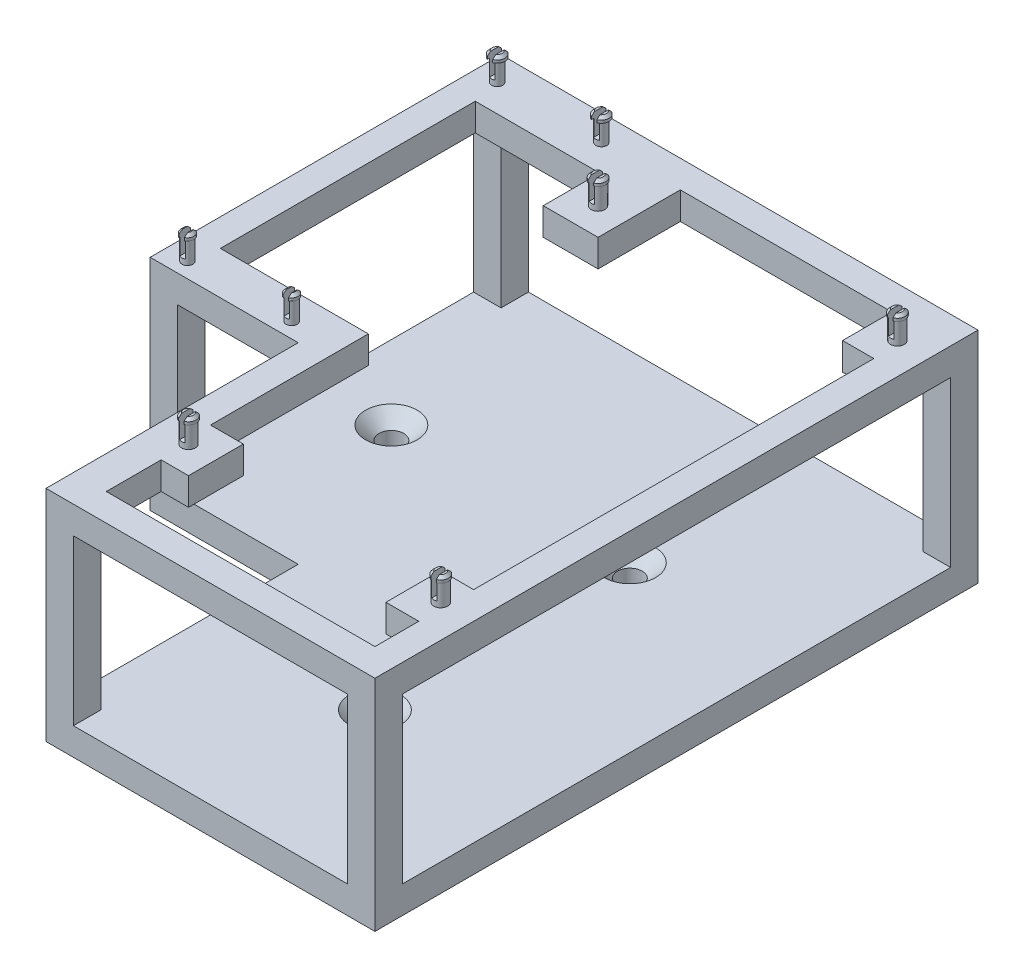
SolidWorks part; units mm, degrees
material "ABS"
ref_plane "Front Plane" through (0, 0, 0) normal (0, 0, 1) x (1, 0, 0)
ref_plane "Top Plane" through (0, 0, 0) normal (0, 1, 0) x (1, 0, 0)
ref_plane "Right Plane" through (0, 0, 0) normal (1, 0, 0) x (0, 0, -1)
sketch "Sketch1" plane through (0, 0, 0) normal (0, 0, 1) x (1, 0, 0)
  line L0 (0, 0) -> (10, 0)
  line L1 (10, 0) -> (55, 2.3584)
  line L2 (55, 2.3584) -> (54.7387, 7.3447)
  line L3 (54.7387, 7.3447) -> (10, 5)
  line L4 (10, 5) -> (5, 5)
  line L5 (0, 0) -> (0, 29)
  line L6 (0, 29) -> (60, 29)
  line L7 (60, 29) -> (60, 24)
  line L8 (60, 24) -> (5, 24)
  line L9 (5, 24) -> (5, 5)
  line L10 (10, 0) -> (45.1286, 0) construction
  point P8 (7.5, 5)
  dimension "D1" = 5
  dimension "D2" = 10
  dimension "D3" = 5
  dimension "D4" = 5
  dimension "D5" = 3
  dimension "D6" = 55
  dimension "D7" = 19
  dimension "D8" = 5
  dimension "D9" = 60
extrude "Boss-Extrude1" add sketch "Sketch1" along normal mid plane 30
sketch "Sketch2" plane through (0, 29, 0) normal (0, 1, 0) x (1, 0, 0)
  line L0 (0, -15) -> (0, 15) construction
  line L1 (0, -55) -> (60, -55)
  line L2 (0, -55) -> (0, 55)
  line L3 (0, 55) -> (60, 55)
  line L4 (60, -55) -> (60, 55)
  line L5 (0, -55) -> (60, 55) construction
  line L6 (0, 55) -> (60, -55) construction
  point P0 (30, 0)
  dimension "D1" = 60
  dimension "D2" = 110
extrude "Boss-Extrude2" add sketch "Sketch2" against normal blind 5
sketch "Sketch3" plane through (0, 29, 0) normal (0, 1, 0) x (1, 0, 0)
  line L1 (56.5, -51) -> (3.5, -51) construction
  line L2 (56.5, -51) -> (56.5, 51) construction
  line L3 (56.5, 51) -> (3.5, 51) construction
  line L4 (3.5, -51) -> (3.5, 51) construction
  line L5 (56.5, -51) -> (3.5, 51) construction
  line L6 (56.5, 51) -> (3.5, -51) construction
  circle A0 centre (54, -37) radius 1.25
  point P0 (30, 0)
  dimension "D5" = 2.5
  dimension "D6" = 2.5
  dimension "D1" = 102
  dimension "D2" = 53
  dimension "D3" = 30
  dimension "D7" = 14
extrude "Boss-Extrude3" add sketch "Sketch3" along normal blind 4
ref_plane "Plane1" through (30, 0, 0) normal (1, 0, 0) x (0, 0, -1)
sketch "Sketch4" plane through (0, 33, 0) normal (0, 1, 0) x (1, 0, 0)
  circle A0 centre (54, -37) radius 1.405
  dimension "D1" = 2.81
extrude "Boss-Extrude4" add sketch "Sketch4" along normal blind 1
chamfer "Chamfer1" distance 0.5 angle 45 1 edges at (54, 34, 38.405)
sketch "Sketch5" plane through (0, 34, 0) normal (0, 1, 0) x (1, 0, 0)
  line L1 (53.5, -38.6304) -> (54.5, -38.6304)
  line L2 (53.5, -38.6304) -> (53.5, -35.3696)
  line L3 (53.5, -35.3696) -> (54.5, -35.3696)
  line L4 (54.5, -38.6304) -> (54.5, -35.3696)
  line L5 (53.5, -38.6304) -> (54.5, -35.3696) construction
  line L6 (53.5, -35.3696) -> (54.5, -38.6304) construction
  point P0 (54, -37)
  dimension "D1" = 1
extrude "Cut-Extrude1" cut sketch "Sketch5" against normal blind 4
sketch "Sketch7" plane through (0, 29, 0) normal (0, 1, 0) x (1, 0, 0)
  line L1 (3.2, 51) -> (56.8, 51) construction
  line L2 (3.2, 51) -> (3.2, -51) construction
  line L4 (56.8, 51) -> (56.8, -51) construction
  line L5 (3.2, 51) -> (56.8, -51) construction
  line L6 (3.2, -51) -> (56.8, 51) construction
  line L7 (3.2, -51) -> (56.8, -51) construction
  circle A0 centre (54.3, 46) radius 1.25
  circle A1 centre (5.7, 40) radius 1.25
  circle A2 centre (54, -37) radius 1.25 construction
  circle A3 centre (54, -37) radius 1.25 construction
  point P0 (30, 0)
  dimension "D5" = 2.5
  dimension "D6" = 2.5
  dimension "D2" = 30
  dimension "D3" = 102
  dimension "D4" = 53.6
  dimension "D7" = 2.5
  dimension "D8" = 5
  dimension "D9" = 11
  dimension "D10" = 2.5
extrude "Boss-Extrude5" add sketch "Sketch7" along normal blind 4
sketch "Sketch8" plane through (0, 33, 0) normal (0, 1, 0) x (1, 0, 0)
  circle A0 centre (5.7, 40) radius 1.405
  circle A1 centre (54.3, 46) radius 1.405
  dimension "D1" = 2.81
  dimension "D2" = 2.81
extrude "Boss-Extrude6" add sketch "Sketch8" along normal blind 1
chamfer "Chamfer2" distance 0.5 angle 45 2 edges at (54.3, 34, -44.595) (5.7, 34, -38.595)
sketch "Sketch9" plane through (0, 34, 0) normal (0, 1, 0) x (1, 0, 0)
  line L1 (5.2, 42.0497) -> (6.2, 42.0497)
  line L2 (5.2, 42.0497) -> (5.2, 37.9503)
  line L3 (5.2, 37.9503) -> (6.2, 37.9503)
  line L4 (6.2, 42.0497) -> (6.2, 37.9503)
  line L5 (5.2, 42.0497) -> (6.2, 37.9503) construction
  line L6 (5.2, 37.9503) -> (6.2, 42.0497) construction
  line L7 (53.8, 43.593) -> (54.8, 43.593)
  line L8 (53.8, 43.593) -> (53.8, 48.407)
  line L9 (53.8, 48.407) -> (54.8, 48.407)
  line L10 (54.8, 43.593) -> (54.8, 48.407)
  line L11 (53.8, 43.593) -> (54.8, 48.407) construction
  line L12 (53.8, 48.407) -> (54.8, 43.593) construction
  point P0 (5.7, 40)
  point P5 (54.3, 46)
  dimension "D1" = 1
  dimension "D2" = 1
extrude "Cut-Extrude2" cut sketch "Sketch9" against normal blind 4
sketch "Sketch10" plane through (0, 29, 0) normal (0, 1, 0) x (1, 0, 0)
  line L0 (4.75, -35) -> (4.75, -28.2355) construction
  line L1 (0, -55) -> (0, 55) construction
  line L2 (55.25, -37) -> (55.25, -32.1392) construction
  circle A0 centre (6, -35) radius 1.25
  circle A1 centre (5.7, 40) radius 1.405 construction
  circle A2 centre (54, -37) radius 1.25 construction
  circle A3 centre (54, -37) radius 1.25 construction
  dimension "D1" = 2.81
  dimension "D3" = 2.5
  dimension "D2" = 75
  dimension "D4" = 4.75
extrude "Boss-Extrude7" add sketch "Sketch10" along normal blind 4
sketch "Sketch11" plane through (0, 33, 0) normal (0, 1, 0) x (1, 0, 0)
  circle A0 centre (6, -35) radius 1.405
  dimension "D1" = 2.81
extrude "Boss-Extrude8" add sketch "Sketch11" along normal blind 1
chamfer "Chamfer3" distance 0.5 angle 45 1 edges at (6, 34, 36.405)
sketch "Sketch12" plane through (0, 34, 0) normal (0, 1, 0) x (1, 0, 0)
  line L1 (6.5, -36.8935) -> (5.5, -36.8935)
  line L2 (6.5, -36.8935) -> (6.5, -33.1065)
  line L3 (6.5, -33.1065) -> (5.5, -33.1065)
  line L4 (5.5, -36.8935) -> (5.5, -33.1065)
  line L5 (6.5, -36.8935) -> (5.5, -33.1065) construction
  line L6 (6.5, -33.1065) -> (5.5, -36.8935) construction
  point P0 (6, -35)
  dimension "D1" = 1
extrude "Cut-Extrude3" cut sketch "Sketch12" against normal blind 4
sketch "Sketch13" plane through (0, 24, 0) normal (0, -1, 0) x (1, 0, 0)
  line L0 (0, 15) -> (0, -15)
  line L8 (5, 15) -> (5, -15)
  line L9 (5, -15) -> (0, -15)
  line L10 (0, -15) -> (0, -55)
  line L11 (0, -55) -> (60, -55)
  line L12 (60, -55) -> (60, 55)
  line L13 (60, 55) -> (0, 55)
  line L14 (0, 55) -> (0, 15)
  line L15 (0, 15) -> (5, 15)
  line L18 (0, -15) -> (0, -55)
  line L19 (0, -55) -> (60, -55)
  line L20 (60, -55) -> (60, 55)
  line L21 (60, 55) -> (0, 55)
  line L22 (0, 55) -> (0, 15)
  dimension "D1" = 0
sketch "Sketch14" plane through (0, 29, 0) normal (0, 1, 0) x (1, 0, 0)
  line L1 (0, 55) -> (-27, 55)
  line L2 (0, 55) -> (0, -9)
  line L3 (0, -9) -> (-27, -9)
  line L4 (-27, 55) -> (-27, -9)
  dimension "D1" = 27
  dimension "D2" = 64
extrude "Boss-Extrude9" add sketch "Sketch14" against normal up to surface (5 mm away) up to face at (16.25, 24, 0)
extrude "Cut-Extrude6" cut sketch "Sketch13" along normal through all
sketch "Sketch15" plane through (0, 29, 0) normal (0, 1, 0) x (1, 0, 0)
  line L0 (-13.5, -9) -> (-13.5, -3.914) construction
  line L1 (0, -9) -> (-27, -9) construction
  line L2 (0, -9) -> (0, 55) construction
  line L3 (0, 55) -> (-27, 55) construction
  line L4 (-27, -9) -> (-27, 55) construction
  circle A0 centre (-23, -6.2) radius 1
  circle A1 centre (-4, -6.2) radius 1
  dimension "D1" = 19
  dimension "D3" = 2
  dimension "D4" = 9.5
  dimension "D2" = 2.8
extrude "Boss-Extrude10" add sketch "Sketch15" along normal blind 4
sketch "Sketch16" plane through (0, 33, 0) normal (0, 1, 0) x (1, 0, 0)
  circle A0 centre (-23, -6.2) radius 1.175
  circle A1 centre (-4, -6.2) radius 1.175
  dimension "D1" = 2.35
  dimension "D2" = 2.35
extrude "Boss-Extrude11" add sketch "Sketch16" along normal blind 1
chamfer "Chamfer4" distance 0.5 angle 45 2 edges at (-4, 34, 7.375) (-23, 34, 7.375)
sketch "Sketch17" plane through (0, 34, 0) normal (0, 1, 0) x (1, 0, 0)
  line L1 (-23.5, -7.7946) -> (-22.5, -7.7946)
  line L2 (-23.5, -7.7946) -> (-23.5, -4.6054)
  line L3 (-23.5, -4.6054) -> (-22.5, -4.6054)
  line L4 (-22.5, -7.7946) -> (-22.5, -4.6054)
  line L5 (-23.5, -7.7946) -> (-22.5, -4.6054) construction
  line L6 (-23.5, -4.6054) -> (-22.5, -7.7946) construction
  line L7 (-4.5, -7.7946) -> (-3.5, -7.7946)
  line L8 (-4.5, -7.7946) -> (-4.5, -4.6054)
  line L9 (-4.5, -4.6054) -> (-3.5, -4.6054)
  line L10 (-3.5, -7.7946) -> (-3.5, -4.6054)
  line L11 (-4.5, -7.7946) -> (-3.5, -4.6054) construction
  line L12 (-4.5, -4.6054) -> (-3.5, -7.7946) construction
  point P0 (-23, -6.2)
  point P5 (-4, -6.2)
  dimension "D1" = 1
  dimension "D2" = 1
extrude "Cut-Extrude7" cut sketch "Sketch17" against normal blind 4
sketch "Sketch20" plane through (0, 29, 0) normal (0, 1, 0) x (1, 0, 0)
  line L0 (-13.5, -9) -> (-13.5, 55) construction
  line L1 (-27, -9) -> (0, -9) construction
  line L2 (60, 55) -> (-27, 55) construction
  circle A0 centre (-23, -6.2) radius 1 construction
  circle A1 centre (-23, -6.2) radius 1 construction
  circle A2 centre (-23, 50.3) radius 1
  circle A3 centre (-4, 50.3) radius 1
  dimension "D1" = 2
  dimension "D2" = 2
  dimension "D3" = 56.5
  dimension "D4" = 9.5
  dimension "D5" = 19
extrude "Boss-Extrude12" add sketch "Sketch20" along normal blind 4
sketch "Sketch21" plane through (0, 33, 0) normal (0, 1, 0) x (1, 0, 0)
  circle A0 centre (-23, 50.3) radius 1.405
  circle A1 centre (-4, 50.3) radius 1.405
  dimension "D1" = 2.81
extrude "Boss-Extrude13" add sketch "Sketch21" along normal blind 1
chamfer "Chamfer5" distance 0.5 angle 45 2 edges at (-4, 34, -48.895) (-23, 34, -48.895)
sketch "Sketch23" plane through (0, 34, 0) normal (0, 1, 0) x (1, 0, 0)
  line L1 (-23.5, 48.1887) -> (-22.5, 48.1887)
  line L2 (-23.5, 48.1887) -> (-23.5, 52.4113)
  line L3 (-23.5, 52.4113) -> (-22.5, 52.4113)
  line L4 (-22.5, 48.1887) -> (-22.5, 52.4113)
  line L5 (-23.5, 48.1887) -> (-22.5, 52.4113) construction
  line L6 (-23.5, 52.4113) -> (-22.5, 48.1887) construction
  line L7 (-4.5, 48.1887) -> (-3.5, 48.1887)
  line L8 (-4.5, 48.1887) -> (-4.5, 52.4113)
  line L9 (-4.5, 52.4113) -> (-3.5, 52.4113)
  line L10 (-3.5, 48.1887) -> (-3.5, 52.4113)
  line L11 (-4.5, 48.1887) -> (-3.5, 52.4113) construction
  line L12 (-4.5, 52.4113) -> (-3.5, 48.1887) construction
  point P0 (-23, 50.3)
  point P5 (-4, 50.3)
  dimension "D1" = 1
  dimension "D2" = 1
extrude "Cut-Extrude8" cut sketch "Sketch23" against normal blind 4
sketch "Sketch18" plane through (0, 29, 0) normal (0, 1, 0) x (1, 0, 0)
  line L1 (-22, 45.3) -> (0.7, 45.3)
  line L2 (0.7, 45.3) -> (0.7, 35)
  line L3 (0.7, 35) -> (10.7, 35)
  line L4 (10.7, 35) -> (10.7, 50)
  line L5 (10.7, 50) -> (49.3, 50)
  line L7 (49.3, 50) -> (49.3, 41)
  line L12 (49.3, 41) -> (55, 41)
  line L13 (55, 41) -> (55, -32)
  line L17 (55, -32) -> (49, -32)
  line L34 (49, -32) -> (49, -42)
  line L35 (49, -42) -> (55, -42)
  line L36 (55, -42) -> (55, -50)
  line L37 (55, -50) -> (6, -50)
  line L38 (6, -50) -> (6, -40)
  line L39 (6, -40) -> (11, -40)
  line L40 (11, -40) -> (11, -30)
  line L41 (11, -30) -> (5, -30)
  line L42 (5, -30) -> (5, -1.2)
  line L43 (5, -1.2) -> (-22, -1.2)
  line L47 (-22, -1.2) -> (-22, 45.3)
  line L48 (-27, 55) -> (-27, -9) construction
  line L49 (60, -55) -> (60, 55) construction
  line L50 (60, 55) -> (-27, 55) construction
  line L51 (0, -55) -> (60, -55) construction
  line L52 (0, -55) -> (0, -9) construction
  circle A0 centre (54.3, 46) radius 1.25 construction
  circle A1 centre (54, -37) radius 1.25 construction
  circle A2 centre (6, -35) radius 1.25 construction
  circle A3 centre (-4, -6.2) radius 1 construction
  circle A4 centre (-23, -6.2) radius 1 construction
  circle A5 centre (-23, 50.3) radius 1 construction
  circle A6 centre (5.7, 40) radius 1.25 construction
  circle A7 centre (-4, 50.3) radius 1 construction
  circle A8 centre (54.3, 46) radius 1.25 construction
  circle A9 centre (54, -37) radius 1.25 construction
  circle A10 centre (6, -35) radius 1.25 construction
  circle A11 centre (-4, -6.2) radius 1 construction
  circle A12 centre (-23, -6.2) radius 1 construction
  circle A13 centre (-23, 50.3) radius 1 construction
  circle A14 centre (5.7, 40) radius 1.25 construction
  circle A15 centre (-4, 50.3) radius 1 construction
  dimension "D12" = 5
  dimension "D2" = 5
  dimension "D3" = 5
  dimension "D4" = 5
  dimension "D5" = 5
  dimension "D6" = 5
  dimension "D7" = 5
  dimension "D8" = 5
  dimension "D9" = 5
  dimension "D10" = 5
  dimension "D11" = 5
  dimension "D1" = 5
  dimension "D13" = 5
  dimension "D14" = 5
  dimension "D15" = 5
  dimension "D16" = 5
  dimension "D17" = 5
  dimension "D18" = 5
  dimension "D19" = 5
extrude "Cut-Extrude9" cut sketch "Sketch18" against normal through all
sketch "Sketch26" plane through (0, 24, 0) normal (0, -1, 0) x (1, 0, 0)
  line L0 (0, 55) -> (5, 55)
  line L1 (0, 55) -> (60, 55) construction
  line L2 (5, 55) -> (5, 50)
  line L3 (5, 50) -> (0, 50)
  line L4 (0, 9) -> (0, 55) construction
  line L5 (0, 50) -> (0, 55)
  line L7 (60, 55) -> (55, 55)
  line L8 (60, 55) -> (60, 50)
  line L9 (60, 50) -> (55, 50)
  line L10 (55, 55) -> (55, 50)
  line L11 (60, -55) -> (55, -55)
  line L12 (60, -55) -> (60, -50)
  line L13 (60, -50) -> (55, -50)
  line L14 (55, -55) -> (55, -50)
  line L15 (-27, -55) -> (-22, -55)
  line L16 (-27, -55) -> (-27, -50)
  line L17 (-27, -50) -> (-22, -50)
  line L18 (-22, -55) -> (-22, -50)
  line L19 (-27, 9) -> (-22, 9)
  line L20 (-27, 9) -> (-27, 4)
  line L21 (-27, 4) -> (-22, 4)
  line L22 (-22, 9) -> (-22, 4)
  dimension "D1" = 5
  dimension "D2" = 5
  dimension "D3" = 5
  dimension "D4" = 5
  dimension "D5" = 5
  dimension "D6" = 5
  dimension "D7" = 5
  dimension "D8" = 5
  dimension "D9" = 5
  dimension "D10" = 5
extrude "Boss-Extrude15" add sketch "Sketch26" along normal blind 30
sketch "Sketch27" plane through (0, -6, 0) normal (0, -1, 0) x (1, 0, 0)
  line L181 (0, 55) -> (60, 55)
  line L182 (0, 55) -> (0, 9)
  line L183 (0, -55) -> (60, -55)
  line L184 (60, 55) -> (60, -55)
  line L185 (-27, 9) -> (0, 9)
  line L186 (-27, 9) -> (-27, -55)
  line L187 (-27, -55) -> (0, -55)
extrude "Boss-Extrude16" add sketch "Sketch27" along normal blind 5
sketch "Sketch28" plane through (0, -6, 0) normal (0, 1, 0) x (1, 0, 0)
  line L0 (60, 55) -> (-27, 55) construction
  line L1 (-27, 55) -> (-27, -9) construction
  line L2 (30, -55) -> (30, 55) construction
  line L3 (0, -55) -> (60, -55) construction
  circle A0 centre (-13.5, 21.5) radius 2.05 construction
  circle A1 centre (30, 21.5) radius 2.05 construction
  circle A2 centre (30, -25) radius 2.05 construction
  dimension "D1" = 33.5
  dimension "D3" = 4.1
  dimension "D4" = 30
  dimension "D2" = 13.5
hole_wizard "CSK for M4 Flat Head Machine Screw2" positions "Sketch35" profile "Sketch36" countersink size "M4" standard "ANSI Metric"
sketch "Sketch35" plane through (0, -6, 0) normal (0, 1, 0) x (1, 0, 0)
  point P0 (-13.5, 21.5)
  point P3 (30, 21.5)
  point P6 (30, -25)
sketch "Sketch36" plane through (-13.5, -6, -21.5) normal (1, 0, 0) x (0, 0, 1)
  line L0 (0, 0) -> (0, 6.3519)
  line L1 (0, 6.3519) -> (2.25, 5)
  line L2 (2.25, 5) -> (2.25, 2.45)
  line L3 (2.25, 2.45) -> (4.7, 0)
  line L5 (4.7, 0) -> (0, 0)
  line L6 (-2.25, 2.45) -> (-4.7, 0) construction
  line L10 (0, 6.3519) -> (-2.25, 5) construction
  line L11 (0, -6.35) -> (0, 107.95) construction
  dimension "Hole Dia." = 4.5
  dimension "Hole Depth" = 5
  dimension "Near C'Sink Dia." = 9.4
  dimension "Near C'Sink Angle" = 90
  dimension "Drill Angle" = 118
